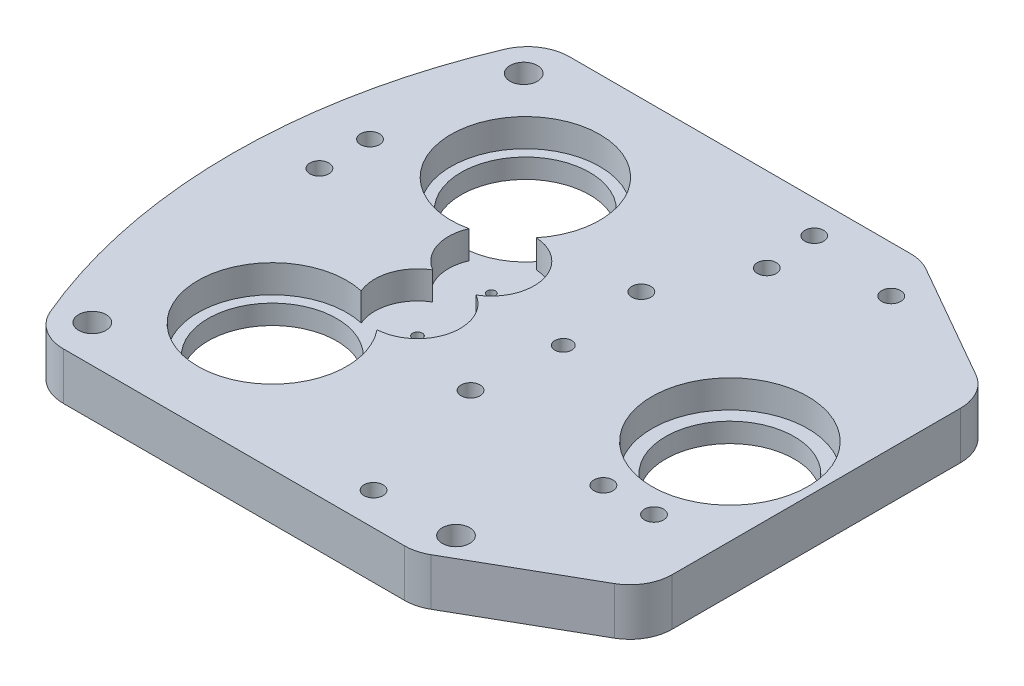
SolidWorks part; units mm, degrees
ref_plane "Front" through (0, 0, 0) normal (0, 0, 1) x (1, 0, 0)
ref_plane "Top" through (0, 0, 0) normal (0, 1, 0) x (1, 0, 0)
ref_plane "Right" through (0, 0, 0) normal (1, 0, 0) x (0, 0, -1)
sketch "Sketch1" plane through (0, 0, 0) normal (0, 1, 0) x (1, 0, 0)
  line L0 (62.5, 0) -> (-58.6146, 0) construction
  line L1 (-62.5, -60) -> (62.5, -60)
  line L2 (-62.5, -60) -> (-62.5, 60)
  line L3 (-62.5, 60) -> (62.5, 60)
  line L4 (62.5, -60) -> (62.5, 60)
  line L5 (-62.5, -60) -> (62.5, 60) construction
  line L6 (-62.5, 60) -> (62.5, -60) construction
  line L7 (-58.6146, 67.5) -> (-58.6146, -67.5) construction
  arc A0 (-58.6146, 67.5) -> (-58.6146, -67.5) centre (62.5, 0) ccw
  point P0 (0, 0)
  dimension "D1" = 125
  dimension "D2" = 120
  dimension "D3" = 135
extrude "Test_Base_Postion" add sketch "Sketch1" along normal blind 11.215 contours L2 A0 | L1 L4 L3 L2
sketch "Fingers_Position" plane through (0, 11.215, 0) normal (0, 1, 0) x (1, 0, 0)
  line L0 (-76.1542, 0) -> (62.5, 0) construction
  line L1 (-26.75, -24.75) -> (-26.75, -56.75) construction
  line L2 (-26.75, 24.75) -> (-26.75, 56.75) construction
  line L3 (-36.5, 12.5) -> (-36.5, -12.5) construction
  line L8 (5.25, -56.75) -> (-49.5, -56.75) construction
  line L9 (5.25, -56.75) -> (5.25, -24.75) construction
  line L10 (5.25, -24.75) -> (-49.5, -24.75) construction
  line L11 (-49.5, -56.75) -> (-49.5, -24.75) construction
  line L12 (5.25, -40.75) -> (-36.5, -40.75) construction
  line L13 (-21.75, -24.75) -> (-21.75, -56.75) construction
  line L14 (-36.5, -40.75) -> (-36.5, -30) construction
  line L15 (42, -29) -> (42, 0) construction
  line L16 (15.25, 44.5) -> (15.25, -10.5) construction
  line L17 (15.25, -10.5) -> (47.25, -10.5) construction
  line L18 (47.25, -10.5) -> (47.25, 44.5) construction
  line L19 (47.25, 44.5) -> (15.25, 44.5) construction
  line L20 (30, 9) -> (30, -29) construction
  line L21 (30, -29) -> (54, -29) construction
  line L22 (54, -29) -> (54, 9) construction
  line L23 (54, 9) -> (30, 9) construction
  line L24 (31.25, 44.5) -> (31.25, 0) construction
  line L25 (31.25, 0) -> (42, 0) construction
  line L26 (-21.75, 24.75) -> (-21.75, 56.75) construction
  line L27 (-49.5, 56.75) -> (-49.5, 24.75) construction
  line L28 (5.25, 24.75) -> (-49.5, 24.75) construction
  line L29 (5.25, 56.75) -> (5.25, 24.75) construction
  line L30 (5.25, 56.75) -> (-49.5, 56.75) construction
  line L31 (15.25, 17.5) -> (47.25, 17.5) construction
  line L32 (62.5, -60) -> (62.5, 60) construction
  line L33 (30, -24) -> (36, -24) construction
  line L34 (36, -24) -> (36, -29) construction
  circle A0 centre (-36.5, -30) radius 16.25 construction
  circle A1 centre (-36.5, -30) radius 17.5 construction
  circle A5 centre (-36.5, -30) radius 15 construction
  circle A6 centre (42, 0) radius 17.75 construction
  circle A7 centre (42, 0) radius 9 construction
  circle A8 centre (-23.3304, -8.75) radius 7.5 construction
  circle A9 centre (-23.3304, -8.75) radius 8.75 construction
  circle A10 centre (-23.3304, -8.75) radius 10 construction
  circle A11 centre (-23.3304, 8.75) radius 10 construction
  circle A12 centre (-23.3304, 8.75) radius 8.75 construction
  circle A13 centre (-23.3304, 8.75) radius 7.5 construction
  circle A14 centre (-36.5, 30) radius 15 construction
  circle A15 centre (-36.5, 30) radius 17.5 construction
  circle A16 centre (-36.5, 30) radius 16.25 construction
  circle A18 centre (-36.5, -30) radius 1 construction
  circle A19 centre (-36.5, 30) radius 1 construction
  arc A20 (-62.5, 60) -> (-62.5, -60) centre (62.5, 0) ccw construction
  circle A21 centre (36, -24) radius 2.25 construction
  circle A22 centre (48, -24) radius 2.25 construction
  dimension "D1" = 32.5
  dimension "D2" = 35
  dimension "D8" = 30
  dimension "D7" = 18
  dimension "D9" = 35.5
  dimension "D3" = 20
  dimension "D4" = 17.5
  dimension "D16" = 15
  dimension "D18" = 2
  dimension "D26" = 4.5
  dimension "D5" = 54.75
  dimension "D6" = 32
  dimension "D10" = 24
  dimension "D11" = 32
  dimension "D12" = 55
  dimension "D15" = 10
  dimension "D19" = 41.75
  dimension "D17" = 10.75
  dimension "D20" = 25
  dimension "D21" = 27
  dimension "D22" = 29
  dimension "D14" = 44.5
  dimension "D23" = 10.75
  dimension "D24" = 27
  dimension "D13" = 8.5
  dimension "D25" = 32
  dimension "D27" = 6
  dimension "D28" = 5
sketch "Thumb_Position" plane through (0, 11.215, 0) normal (0, 1, 0) x (1, 0, 0)
  line L12 (-76.1542, 0) -> (62.5, 0) construction
  circle A0 centre (42, 0) radius 17.75 construction
  circle A1 centre (42, 0) radius 9 construction
  dimension "D1" = 18
  dimension "D2" = 35.5
sketch "Intermediate_Gear_Position" plane through (0, 11.215, 0) normal (0, 1, 0) x (1, 0, 0)
  line L0 (-62.75, 25.4139) -> (-62.75, 19.4139) construction
  line L1 (-29.75, 25.4139) -> (-29.75, 1.4139) construction
  line L2 (-29.75, 25.4139) -> (-67.75, 25.4139) construction
  line L3 (-67.75, 25.4139) -> (-67.75, 1.4139) construction
  line L4 (-29.75, 1.4139) -> (-67.75, 1.4139) construction
  line L5 (-67.75, 13.4139) -> (-38.75, 13.4139) construction
  line L6 (-26.75, 24.75) -> (-26.75, 56.75) construction
  line L7 (-62.75, 19.4139) -> (-67.75, 19.4139) construction
  circle A3 centre (-23.3304, -8.75) radius 14 construction
  circle A6 centre (-38.75, 13.4139) radius 13 construction
  circle A7 centre (-62.75, 19.4139) radius 2.25 construction
  circle A8 centre (-62.75, 7.4139) radius 2.25 construction
  dimension "D6" = 28
  dimension "D11" = 26
  dimension "D5" = 4.5
  dimension "D1" = 24
  dimension "D2" = 38
  dimension "D4" = 29
  dimension "D3" = 3
  dimension "D7" = 6
  dimension "D8" = 5
sketch "Sketch10" plane through (0, 11.215, 0) normal (0, 1, 0) x (1, 0, 0)
  circle A0 centre (-36.5, 30) radius 15.25
  circle A1 centre (-36.5, -30) radius 15.25
  circle A2 centre (42, 0) radius 15.25
  dimension "D1" = 30.5
extrude "Connect_Finger_Holes" cut sketch "Sketch10" against normal through all
sketch "Sketch11" plane through (0, 11.215, 0) normal (0, 1, 0) x (1, 0, 0)
  circle A0 centre (42, 0) radius 18.5
  dimension "D1" = 37
extrude "XL320_Finger_Knuckle_Mount" cut sketch "Sketch11" against normal blind 6.6025
sketch "Sketch24" plane through (0, 11.215, 0) normal (0, 1, 0) x (1, 0, 0)
  line L0 (5.25, -24.75) -> (5.25, -20.25) construction
  line L1 (5.25, -20.25) -> (0.75, -20.25) construction
  line L2 (5.25, -56.75) -> (9.75, -56.75) construction
  line L3 (5.25, -56.75) -> (-49.5, -56.75) construction
  line L4 (9.75, -56.75) -> (9.75, -52.25) construction
  line L5 (5.25, 24.75) -> (5.25, 20.25) construction
  line L6 (5.25, 20.25) -> (0.75, 20.25) construction
  line L7 (5.25, 56.75) -> (9.75, 56.75) construction
  line L8 (5.25, 56.75) -> (-49.5, 56.75) construction
  line L9 (9.75, 56.75) -> (9.75, 52.25) construction
  line L10 (15.25, 44.5) -> (10.75, 44.5) construction
  line L11 (10.75, 44.5) -> (10.75, 40) construction
  line L12 (31.25, 44.5) -> (31.25, 49) construction
  line L13 (47.25, 44.5) -> (15.25, 44.5) construction
  circle A0 centre (9.75, 52.25) radius 2.25
  circle A1 centre (0.75, 20.25) radius 2.25
  circle A2 centre (0.75, -20.25) radius 2.25
  circle A3 centre (9.75, -52.25) radius 2.25
  circle A4 centre (10.75, 40) radius 2.25
  circle A5 centre (31.25, 49) radius 2.25
  dimension "D2" = 4.5
  dimension "D1" = 4.5
extrude "AX12_Mount_Holes_(M4)" cut sketch "Sketch24" against normal through all
sketch "Sketch21" plane through (0, 11.215, 0) normal (0, 1, 0) x (1, 0, 0)
  circle A0 centre (-36.5, 30) radius 17.65
  circle A1 centre (-23.3304, 8.75) radius 10.15
  circle A2 centre (-23.3304, -8.75) radius 10.15
  circle A3 centre (-36.5, -30) radius 17.65
  dimension "D1" = 20.3
  dimension "D2" = 35.3
extrude "Gears_Holes" cut sketch "Sketch21" against normal blind 6.6025 contours A0 | A1 | A2 | A3
sketch "Sketch22" plane through (0, 4.6125, 0) normal (0, 1, 0) x (1, 0, 0)
  circle A1 centre (-23.3304, -8.75) radius 1.15
  dimension "D1" = 2.3
extrude "Gears_Rod_Holes" cut sketch "Sketch22" against normal blind 3
sketch "Sketch28" plane through (0, 4.6125, 0) normal (0, 1, 0) x (1, 0, 0)
  circle A0 centre (-23.3304, 8.75) radius 1
  dimension "D1" = 2
sketch "Sketch29" plane through (0, 11.215, 0) normal (0, 1, 0) x (1, 0, 0)
  line L0 (27.5, 60) -> (62.5, 40)
  line L1 (-62.5, 60) -> (62.5, 60) construction
  line L2 (62.5, -60) -> (62.5, 60) construction
  line L3 (62.5, 40) -> (62.5, 60)
  line L4 (62.5, 60) -> (27.5, 60)
  line L5 (62.5, 0) -> (-76.1542, 0) construction
  line L6 (62.5, -60) -> (27.5, -60)
  line L7 (62.5, -40) -> (62.5, -60)
  line L8 (27.5, -60) -> (62.5, -40)
  dimension "D1" = 35
  dimension "D2" = 20
extrude "Cut-Extrude1" cut sketch "Sketch29" against normal through all
fillet "Fillet1" radius 10 6 edges at (-62.5, 5.6075, 60) (27.5, 5.6075, 60) (62.5, 5.6075, 40) (62.5, 5.6075, -40) (27.5, 5.6075, -60) (-62.5, 5.6075, -60)
sketch "Sketch17" plane through (0, 11.215, 0) normal (0, 1, 0) x (1, 0, 0)
  line L0 (-58.0408, 51.1529) -> (-61.5696, 58.3326) construction
  line L3 (-76.1542, 0) -> (62.5, 0) construction
  line L4 (-56.0408, 60) -> (-56.0408, -60) construction
  line L6 (-58.0408, 51.1529) -> (-56.0408, 51.1529) construction
  line L7 (24.8444, -60) -> (24.8444, 60) construction
  line L8 (28.8444, -51.7944) -> (24.8444, -51.7944) construction
  line L9 (28.8444, -51.7944) -> (27.411, -59.665) construction
  circle A0 centre (-58.0408, 51.1529) radius 3.25
  circle A1 centre (-58.0408, -51.1529) radius 3.25
  circle A2 centre (28.8444, -51.7944) radius 3.25
  arc A3 (-56.0408, 60) -> (-65.2547, 53.8864) centre (-56.0408, 50) ccw construction
  arc A4 (24.8444, -60) -> (29.8057, -58.6824) centre (24.8444, -50) ccw construction
  dimension "D3" = 6.5
  dimension "D1" = 6.5
  dimension "D2" = 8
  dimension "D4" = 2
  dimension "D5" = 8
  dimension "D6" = 4
extrude "Connect_Holes_(M6)" cut sketch "Sketch17" against normal through all
sketch "Sketch19" plane through (0, 0, 0) normal (0, -1, 0) x (1, 0, 0)
  line L0 (-58.0408, 51.1529) -> (-58.0408, 56.9264) construction
  line L1 (-58.0408, 51.1529) -> (-63.0408, 54.0397) construction
  line L2 (-58.0408, 51.1529) -> (-53.0408, 54.0397) construction
  line L3 (-58.0408, 51.1529) -> (-63.0408, 48.2662) construction
  line L4 (-58.0408, 51.1529) -> (-53.0408, 48.2662) construction
  line L5 (-58.0408, 51.1529) -> (-58.0408, 45.3794) construction
  line L6 (-58.0408, 56.9264) -> (-63.0408, 54.0397)
  line L7 (-63.0408, 54.0397) -> (-63.0408, 48.2662)
  line L8 (-63.0408, 48.2662) -> (-58.0408, 45.3794)
  line L9 (-58.0408, 45.3794) -> (-53.0408, 48.2662)
  line L10 (-53.0408, 48.2662) -> (-53.0408, 54.0397)
  line L11 (-53.0408, 54.0397) -> (-58.0408, 56.9264)
  line L12 (28.8444, 51.7944) -> (28.8444, 57.5679) construction
  line L13 (28.8444, 51.7944) -> (23.8444, 54.6812) construction
  line L14 (28.8444, 51.7944) -> (23.8444, 48.9077) construction
  line L15 (28.8444, 51.7944) -> (28.8444, 46.0209) construction
  line L16 (28.8444, 51.7944) -> (33.8444, 54.6812) construction
  line L17 (28.8444, 51.7944) -> (33.8444, 48.9077) construction
  line L18 (28.8444, 57.5679) -> (23.8444, 54.6812)
  line L19 (23.8444, 54.6812) -> (23.8444, 48.9077)
  line L20 (23.8444, 48.9077) -> (28.8444, 46.0209)
  line L21 (28.8444, 46.0209) -> (33.8444, 48.9077)
  line L22 (33.8444, 48.9077) -> (33.8444, 54.6812)
  line L23 (33.8444, 54.6812) -> (28.8444, 57.5679)
  line L24 (-58.0408, -51.1529) -> (-58.0408, -45.3794) construction
  line L25 (-58.0408, -51.1529) -> (-63.0408, -48.2662) construction
  line L26 (-58.0408, -51.1529) -> (-63.0408, -54.0397) construction
  line L27 (-58.0408, -51.1529) -> (-58.0408, -56.9264) construction
  line L28 (-58.0408, -51.1529) -> (-53.0408, -54.0397) construction
  line L29 (-58.0408, -51.1529) -> (-53.0408, -48.2662) construction
  line L30 (-58.0408, -45.3794) -> (-63.0408, -48.2662)
  line L31 (-63.0408, -48.2662) -> (-63.0408, -54.0397)
  line L32 (-63.0408, -54.0397) -> (-58.0408, -56.9264)
  line L33 (-58.0408, -56.9264) -> (-53.0408, -54.0397)
  line L34 (-53.0408, -54.0397) -> (-53.0408, -48.2662)
  line L35 (-53.0408, -48.2662) -> (-58.0408, -45.3794)
  circle A0 centre (-58.0408, 51.1529) radius 5 construction
  circle A1 centre (28.8444, 51.7944) radius 5 construction
  circle A2 centre (-58.0408, -51.1529) radius 5 construction
  dimension "D1" = 10
  dimension "D2" = 60
  dimension "D3" = 60
  dimension "D6" = 60
  dimension "D7" = 60
  dimension "D9" = 60
  dimension "D10" = 60
extrude "Nuts_(M6)" cut sketch "Sketch19" against normal blind 6
sketch "Sketch27" plane through (0, 0, 0) normal (0, -1, 0) x (1, 0, 0)
  line L0 (9.75, 56.2915) -> (6.25, 54.2707)
  line L1 (6.25, 54.2707) -> (6.25, 50.2293)
  line L2 (6.25, 50.2293) -> (9.75, 48.2085)
  line L3 (9.75, 48.2085) -> (13.25, 50.2293)
  line L4 (13.25, 50.2293) -> (13.25, 54.2707)
  line L5 (13.25, 54.2707) -> (9.75, 56.2915)
  line L6 (6.25, 54.2707) -> (13.25, 50.2293) construction
  line L7 (6.25, 50.2293) -> (13.25, 54.2707) construction
  line L8 (9.75, 56.2915) -> (9.75, 48.2085) construction
  line L11 (-2.75, 22.2707) -> (-2.75, 18.2293)
  line L12 (4.25, 18.2293) -> (4.25, 22.2707)
  line L15 (0.75, 16.2085) -> (4.25, 18.2293)
  line L20 (0.75, 24.2915) -> (0.75, 16.2085) construction
  line L24 (-2.75, 22.2707) -> (4.25, 18.2293) construction
  line L26 (-2.75, 18.2293) -> (0.75, 16.2085)
  line L27 (4.25, 22.2707) -> (0.75, 24.2915)
  line L28 (-2.75, 18.2293) -> (4.25, 22.2707) construction
  line L30 (0.75, 24.2915) -> (-2.75, 22.2707)
  line L38 (-2.75, -18.2293) -> (4.25, -22.2707) construction
  line L40 (-2.75, -22.2707) -> (0.75, -24.2915)
  line L44 (0.75, -24.2915) -> (4.25, -22.2707)
  line L45 (-2.75, -18.2293) -> (-2.75, -22.2707)
  line L46 (-2.75, -22.2707) -> (4.25, -18.2293) construction
  line L53 (4.25, -18.2293) -> (0.75, -16.2085)
  line L54 (0.75, -16.2085) -> (-2.75, -18.2293)
  line L55 (4.25, -22.2707) -> (4.25, -18.2293)
  line L56 (0.75, -16.2085) -> (0.75, -24.2915) construction
  line L57 (6.25, -54.2707) -> (13.25, -50.2293) construction
  line L58 (6.25, -50.2293) -> (6.25, -54.2707)
  line L59 (6.25, -54.2707) -> (9.75, -56.2915)
  line L60 (13.25, -50.2293) -> (9.75, -48.2085)
  line L61 (9.75, -48.2085) -> (6.25, -50.2293)
  line L62 (9.75, -56.2915) -> (13.25, -54.2707)
  line L63 (6.25, -50.2293) -> (13.25, -54.2707) construction
  line L64 (9.75, -48.2085) -> (9.75, -56.2915) construction
  line L65 (13.25, -54.2707) -> (13.25, -50.2293)
  line L66 (14.25, -37.9793) -> (10.75, -35.9585)
  line L67 (10.75, -35.9585) -> (10.75, -44.0415) construction
  line L68 (7.25, -42.0207) -> (14.25, -37.9793) construction
  line L69 (7.25, -37.9793) -> (14.25, -42.0207) construction
  line L70 (7.25, -37.9793) -> (7.25, -42.0207)
  line L71 (10.75, -35.9585) -> (7.25, -37.9793)
  line L72 (7.25, -42.0207) -> (10.75, -44.0415)
  line L73 (14.25, -42.0207) -> (14.25, -37.9793)
  line L74 (10.75, -44.0415) -> (14.25, -42.0207)
  line L75 (27.75, -46.9793) -> (27.75, -51.0207)
  line L76 (27.75, -51.0207) -> (31.25, -53.0415)
  line L77 (34.75, -51.0207) -> (34.75, -46.9793)
  line L78 (34.75, -46.9793) -> (31.25, -44.9585)
  line L79 (27.75, -51.0207) -> (34.75, -46.9793) construction
  line L80 (31.25, -53.0415) -> (34.75, -51.0207)
  line L81 (31.25, -44.9585) -> (31.25, -53.0415) construction
  line L82 (27.75, -46.9793) -> (34.75, -51.0207) construction
  line L83 (31.25, -44.9585) -> (27.75, -46.9793)
  circle A0 centre (9.75, 52.25) radius 3.5 construction
  circle A1 centre (0.75, 20.25) radius 3.5 construction
  circle A3 centre (0.75, 20.25) radius 2.25 construction
  circle A5 centre (0.75, -20.25) radius 3.5 construction
  circle A7 centre (0.75, -20.25) radius 2.25 construction
  circle A9 centre (9.75, -52.25) radius 3.5 construction
  circle A11 centre (9.75, 52.25) radius 2.25 construction
  circle A17 centre (9.75, -52.25) radius 2.25 construction
  circle A18 centre (10.75, -40) radius 3.5 construction
  circle A19 centre (10.75, -40) radius 2.25 construction
  circle A20 centre (31.25, -49) radius 3.5 construction
  circle A21 centre (31.25, -49) radius 2.25 construction
  dimension "D1" = 7
  dimension "D3" = 7
  dimension "D5" = 7
  dimension "D7" = 7
  dimension "D9" = 7
  dimension "D11" = 7
  dimension "D2" = 60
  dimension "D4" = 60
  dimension "D6" = 60
  dimension "D8" = 60
  dimension "D10" = 60
  dimension "D12" = 60
extrude "Nuts_(M4)" cut sketch "Sketch27" against normal blind 5
sketch "Sketch30" plane through (0, 11.215, 0) normal (0, 1, 0) x (1, 0, 0)
  line L0 (62.5, 0) -> (2.5, 0) construction
  line L1 (-76.1542, 0) -> (62.5, 0) construction
  circle A0 centre (2.5, 0) radius 2
  dimension "D1" = 4
  dimension "D2" = 60
extrude "Connect_To_House" cut sketch "Sketch30" against normal through all
sketch "Sketch31" plane through (0, 11.215, 0) normal (0, 1, 0) x (1, 0, 0)
  circle A0 centre (-62.75, 19.4139) radius 2.25
  circle A1 centre (-62.75, 7.4139) radius 2.25
  circle A2 centre (36, -24) radius 2.25
  circle A3 centre (48, -24) radius 2.25
  dimension "D1" = 4.5
extrude "M4_Extension_Hole" cut sketch "Sketch31" against normal blind 5
extrude "M2_Shaft_Hole" cut sketch "Sketch28" against normal blind 3
equation "\"od1\"= 35'outside diameter finger"
equation "\"n1\"= 26'number of teeth finger"
equation "\"m1\"= \"od1\" / ( \"n1\" + 2 )'module finger"
equation "\"p1\"= \"m1\" * pi'pitch finger"
equation "\"d1\"= \"m1\" * \"n1\"'primitive diameter finger"
equation "\"da1\"= \"d1\" + 2 * \"m1\"'head diamater finger"
equation "\"df1\"= \"d1\" - 2 * \"m1\"'foot diameter finger"
equation "\"od2\"= 20'outside diameter intermediate"
equation "\"n2\"= 14'number of teeth intermediate"
equation "\"m2\"= \"od2\" / ( \"n2\" + 2 )'module intermediate"
equation "\"p2\"= \"m2\" * pi'pitch intermediate"
equation "\"d2\"= \"m2\" * \"n2\"'primitive diameter intermediate"
equation "\"da2\"= \"d2\" + 2 * \"m2\"'head diamater intermediate"
equation "\"df2\"= \"d2\" - 2 * \"m2\"'foot diameter intermediate"
equation "\"od3\"= 30'outside diameter top"
equation "\"n3\"= 28'number of teeth top"
equation "\"m3\"= \"od3\" / ( \"n3\" + 2 )'module top"
equation "\"p3\"= \"m3\" * pi'pitch top"
equation "\"d3\"= \"m3\" * \"n3\"'primitive diameter top"
equation "\"da3\"= \"d3\" + 2 * \"m3\"'head diamater top"
equation "\"df3\"= \"d3\" - 2 * \"m3\"'foot diameter top"
equation "\"od4\"= 28'outside diameter drive"
equation "\"n4\"= 26'number of teeth drive"
equation "\"m4\"= \"od4\" / ( \"n4\" + 2 )'module drive"
equation "\"p4\"= \"m4\" * pi'pitch drive"
equation "\"d4\"= \"m4\" * \"n4\"'primitive diameter drive"
equation "\"da4\"= \"d4\" + 2 * \"m4\"'head diamater drive"
equation "\"df4\"= \"d4\" - 2 * \"m4\"'foot diameter drive"
equation "\"D2@Fingers_Position\"=\"da1\""
equation "\"D1@Fingers_Position\"=\"d1\""
equation "\"D8@Fingers_Position\"=\"df1\""
equation "\"D3@Fingers_Position\"=\"da2\""
equation "\"D4@Fingers_Position\"=\"d2\""
equation "\"D6@Intermediate_Gear_Position\"=\"d3\""
equation "\"D16@Fingers_Position\"=\"df2\""
equation "\"D11@Intermediate_Gear_Position\"=\"d4\""
